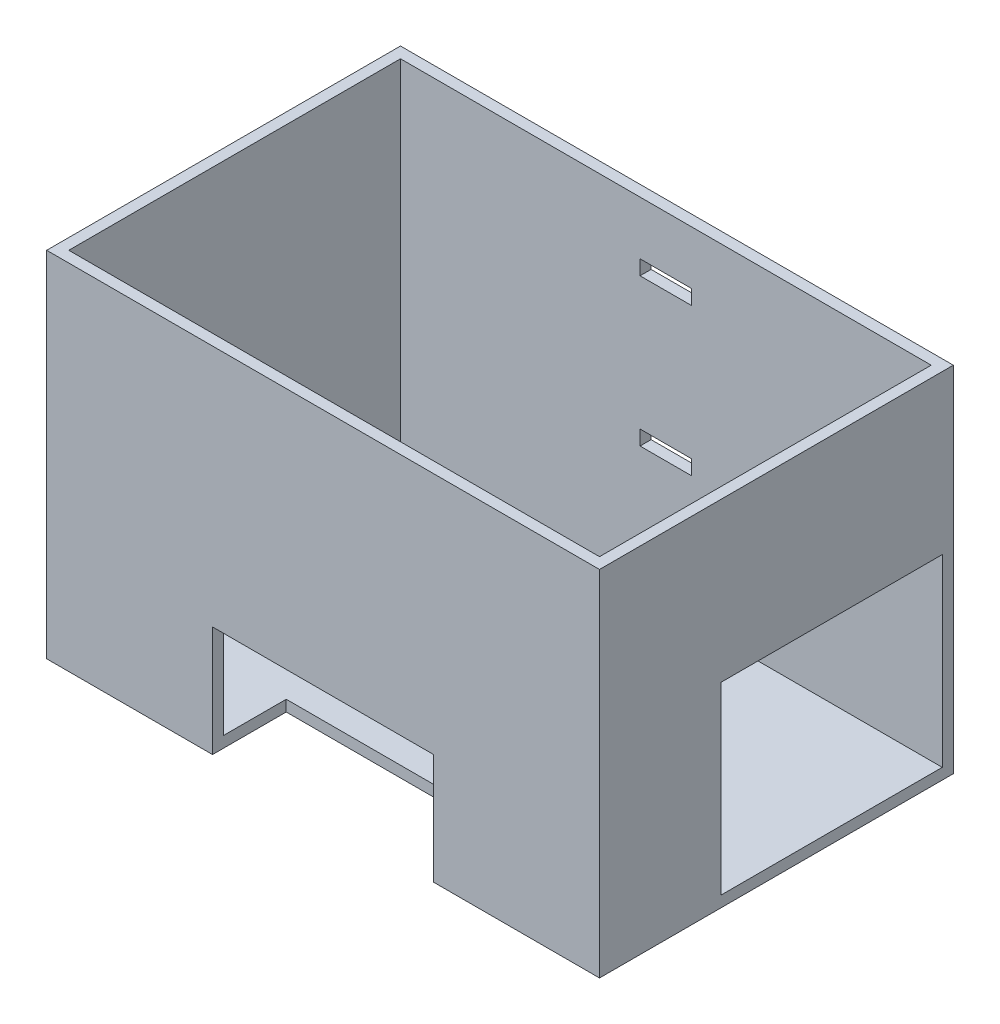
SolidWorks part; units mm, degrees
ref_plane "Front Plane" through (0, 0, 0) normal (0, 0, 1) x (1, 0, 0)
ref_plane "Top Plane" through (0, 0, 0) normal (0, 1, 0) x (1, 0, 0)
ref_plane "Right Plane" through (0, 0, 0) normal (1, 0, 0) x (0, 0, -1)
sketch "Sketch1" plane through (0, 0, 0) normal (0, 1, 0) x (1, 0, 0)
  line L1 (0, 0) -> (75, 0)
  line L2 (0, 0) -> (0, 48)
  line L3 (0, 48) -> (75, 48)
  line L4 (75, 0) -> (75, 48)
  dimension "D1" = 75
  dimension "D2" = 48
extrude "Boss-Extrude1" add sketch "Sketch1" along normal blind 48
shell "Shell1" thickness 1.5
sketch "Sketch2" plane through (75, 0, 0) normal (1, 0, 0) x (0, 0, -1)
  line L6 (48, 48) -> (48, 0) construction
  line L7 (16.5, 26.5) -> (46.5, 26.5)
  line L8 (16.5, 26.5) -> (16.5, 1.5)
  line L9 (16.5, 1.5) -> (46.5, 1.5)
  line L10 (46.5, 26.5) -> (46.5, 1.5)
  line L11 (0, 0) -> (48, 0) construction
  dimension "D1" = 25
  dimension "D2" = 30
  dimension "D3" = 1.5
  dimension "D4" = 1.5
extrude "Cut-Extrude2" cut sketch "Sketch2" against normal blind 50
sketch "Sketch3" plane through (0, 0, 0) normal (0, -1, 0) x (1, 0, 0)
  line L0 (0, 0) -> (75, 0) construction
  line L1 (22.5, -10) -> (52.5, -10)
  line L2 (22.5, -10) -> (22.5, 0)
  line L3 (22.5, 0) -> (52.5, 0)
  line L4 (52.5, -10) -> (52.5, 0)
  point P6 (37.5, -10)
  point P7 (37.5, 0)
  point P9 (37.5, 0)
  dimension "D1" = 30
  dimension "D2" = 10
extrude "Cut-Extrude3" cut sketch "Sketch3" against normal blind 15
sketch "Sketch4" plane through (0, 0, 0) normal (-1, 0, 0) x (0, 0, 1)
  line L0 (0, 48) -> (0, 0) construction
  line L1 (-21.5, 1.5) -> (-1.5, 1.5)
  line L2 (-21.5, 1.5) -> (-21.5, 26.5)
  line L3 (-21.5, 26.5) -> (-1.5, 26.5)
  line L4 (-1.5, 1.5) -> (-1.5, 26.5)
  line L5 (-48, 0) -> (0, 0) construction
  dimension "D1" = 20
  dimension "D2" = 25
  dimension "D3" = 1.5
  dimension "D4" = 1.5
extrude "Cut-Extrude4" cut sketch "Sketch4" against normal blind 15
sketch "Sketch5" plane through (0, 0, -48) normal (0, 0, -1) x (-1, 0, 0)
  line L0 (-75, 0) -> (0, 0) construction
  line L1 (-41, 20.75) -> (-34, 20.75)
  line L2 (-41, 20.75) -> (-41, 18.75)
  line L3 (-41, 18.75) -> (-34, 18.75)
  line L4 (-34, 20.75) -> (-34, 18.75)
  line L5 (-41, 40.75) -> (-41, 38.75)
  line L6 (-41, 40.75) -> (-34, 40.75)
  line L7 (-34, 40.75) -> (-34, 38.75)
  line L8 (-41, 38.75) -> (-34, 38.75)
  point P6 (-37.5, 18.75)
  point P7 (-37.5, 0)
  dimension "D1" = 2
  dimension "D2" = 7
  dimension "D3" = 18.75
  dimension "D4" = 2
extrude "Cut-Extrude5" cut sketch "Sketch5" against normal blind 15
